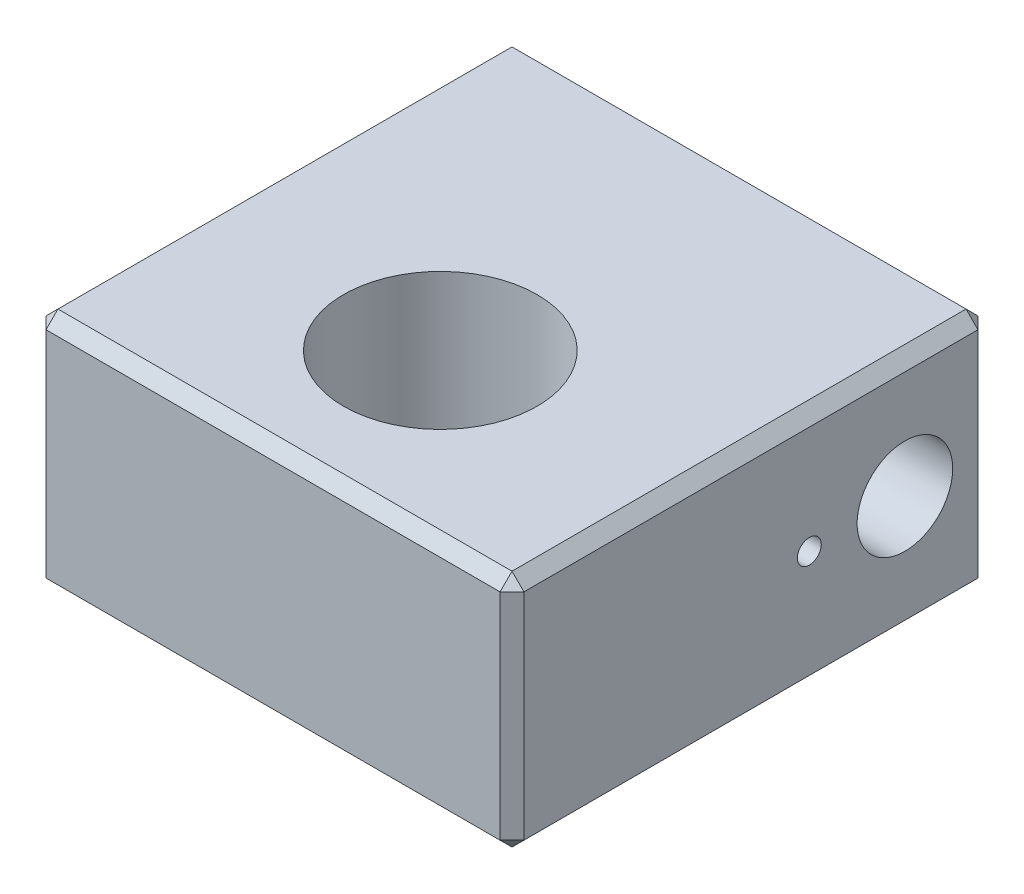
SolidWorks part; units mm, degrees
ref_plane "Front (XY)" through (0, 0, 0) normal (0, 0, 1) x (1, 0, 0)
ref_plane "Top (XZ)" through (0, 0, 0) normal (0, 1, 0) x (1, 0, 0)
ref_plane "Right (YZ)" through (0, 0, 0) normal (1, 0, 0) x (0, 0, -1)
sketch "Sketch1" plane through (0, 0, 0) normal (0, 1, 0) x (1, 0, 0)
  line L1 (-10, 10) -> (10, 10)
  line L2 (-10, 10) -> (-10, -10)
  line L3 (-10, -10) -> (10, -10)
  line L4 (10, 10) -> (10, -10)
  line L5 (-10, 10) -> (10, -10) construction
  line L6 (-10, -10) -> (10, 10) construction
  point P0 (0, 0)
  dimension "D1" = 20
  dimension "D2" = 20
extrude "Boss-Extrude1" add sketch "Sketch1" along normal mid plane 10
sketch "Sketch2" plane through (0, 5, 0) normal (0, 1, 0) x (1, 0, 0)
  circle A0 centre (0, -3) radius 4.05
  dimension "D1" = 8.1
  dimension "D2" = 3
extrude "Cut-Extrude1" cut sketch "Sketch2" against normal through all
sketch "Sketch3" plane through (10, 0, 0) normal (1, 0, 0) x (0, 0, -1)
  circle A0 centre (6.4421, 0) radius 2
  dimension "D1" = 4
extrude "Cut-Extrude2" cut sketch "Sketch3" against normal through all
sketch "Sketch4" plane through (10, 0, 0) normal (1, 0, 0) x (0, 0, -1)
  line L0 (-10, 5) -> (10, 5) construction
  circle A0 centre (2.4421, 0) radius 0.5
  dimension "D1" = 1
  dimension "D2" = 4
  dimension "D3" = 5
extrude "Cut-Extrude3" cut sketch "Sketch4" against normal blind 10
chamfer "Chamfer1" distance 0.5 angle 45 12 edges at (-10, -5, 0) (-10, 0, -10) (0, -5, -10) (10, 0, -10) (0, 5, -10) (-10, 5, 0) (-10, 0, 10) (0, -5, 10) (10, -5, 0) (10, 0, 10) (0, 5, 10) (10, 5, 0)
